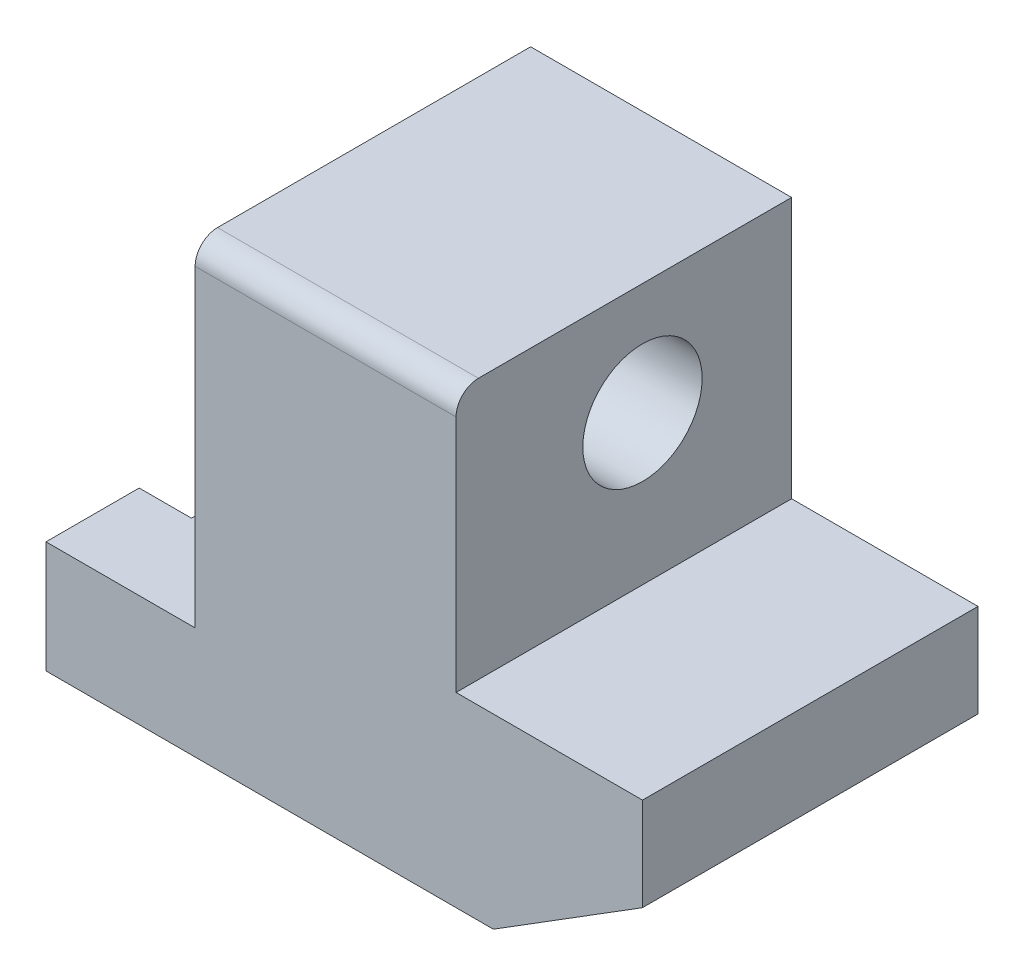
SolidWorks part; units mm, degrees
ref_plane "Plano frontal" through (0, 0, 0) normal (0, 0, 1) x (1, 0, 0)
ref_plane "Plano superior" through (0, 0, 0) normal (0, 1, 0) x (1, 0, 0)
ref_plane "Plano direito" through (0, 0, 0) normal (1, 0, 0) x (0, 0, -1)
sketch "Esboço1" plane through (0, 0, 0) normal (1, 0, 0) x (0, 0, -1)
  line L0 (0, 0) -> (90, 0)
  line L1 (90, 0) -> (90, 30)
  line L2 (90, 30) -> (0, 30)
  line L3 (0, 30) -> (0, 0)
  line L4 (25, 0) -> (25, 30)
  line L5 (25, 30) -> (65, 30)
  line L6 (65, 30) -> (65, 0)
  line L7 (65, 0) -> (25, 0)
  line L8 (0, 30) -> (0, 120)
  line L9 (0, 120) -> (90, 120)
  line L10 (90, 120) -> (90, 30)
  point P7 (0, 15)
  dimension "D1" = 90
  dimension "D2" = 30
  dimension "D3" = 40
  dimension "D4" = 25
  dimension "D5" = 90
extrude "Ressalto-extrusão2" add sketch "Esboço1" along normal blind 40 contours L0 L4 L2 L3 | L2 L6 L0 L1 | L6 L2 L4 L0
sketch "Esboço2" plane through (0, 0, 0) normal (0, 0, 1) x (1, 0, 0)
  line L0 (40, 30) -> (40, 120)
  line L1 (40, 120) -> (110, 120)
  line L2 (110, 120) -> (110, 104.2427)
  line L3 (160, 0) -> (160, 50)
  line L6 (120, 0) -> (40, 0)
  line L7 (40, 0) -> (40, 30)
  line L8 (160, 0) -> (120, 0)
  line L10 (110, 104.2427) -> (110, 50)
  line L11 (110, 50) -> (160, 50)
  dimension "D1" = 70
  dimension "D2" = 120
  dimension "D3" = 50
  dimension "D4" = 90
extrude "Ressalto-extrusão3" add sketch "Esboço2" against normal blind 90
sketch "Esboço3" plane through (40, 0, 0) normal (-1, 0, 0) x (0, 0, 1)
  line L0 (-90, 120) -> (-90, 30) construction
  line L2 (-90, 120) -> (0, 120) construction
  circle A0 centre (-50, 90) radius 16
  point P6 (-48.0334, 120)
  dimension "D1" = 32
  dimension "D2" = 40
  dimension "D3" = 30
extrude "Corte-extrusão1" cut sketch "Esboço3" against normal through all
fillet "Filete1" radius 6 1 edges at (75, 120, 0)
sketch "Esboço4" plane through (0, 0, 0) normal (-1, 0, 0) x (0, 0, 1)
  line L0 (-65, 0) -> (-65, 30)
  line L1 (0, 0) -> (-90, 0) construction
  line L2 (-90, 30) -> (0, 30) construction
  line L3 (-65, 30) -> (-25, 30)
  line L4 (-25, 30) -> (-25, 0)
  line L5 (-25, 0) -> (-65, 0)
  line L6 (-90, 0) -> (-90, 30) construction
  line L7 (0, 30) -> (0, 0) construction
  dimension "D1" = 25
  dimension "D2" = 25
extrude "Corte-extrusão2" cut sketch "Esboço4" against normal blind 14
sketch "Esboço5" plane through (0, 0, 0) normal (0, 0, 1) x (1, 0, 0)
  line L0 (120, 0) -> (160, 25)
  line L1 (160, 0) -> (0, 0) construction
  line L2 (160, 0) -> (160, 50) construction
  line L3 (160, 25) -> (160, 0)
  line L4 (160, 0) -> (120, 0)
  dimension "D1" = 25
  dimension "D2" = 40
extrude "Corte-extrusão3" cut sketch "Esboço5" against normal through all
